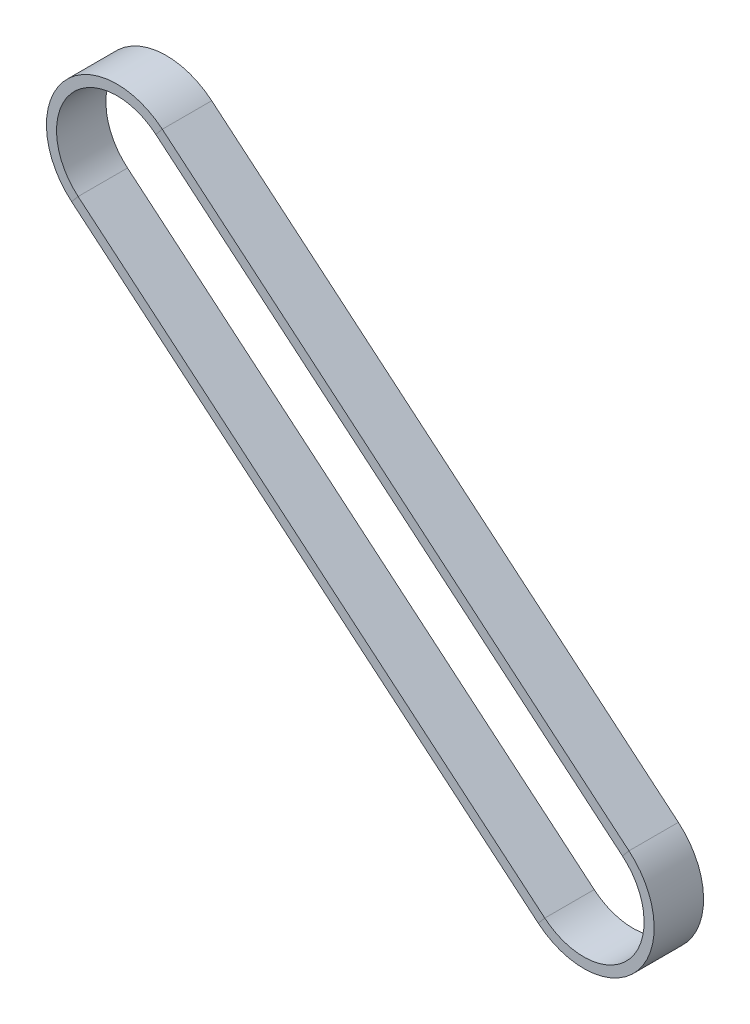
SolidWorks part; units mm, degrees
material "Rubber"
ref_plane "Front Plane" through (0, 0, 0) normal (0, 0, 1) x (1, 0, 0)
ref_plane "Top Plane" through (0, 0, 0) normal (0, 1, 0) x (1, 0, 0)
ref_plane "Right Plane" through (0, 0, 0) normal (1, 0, 0) x (0, 0, -1)
sketch "Sketch2" plane through (0, 0, 0) normal (0, 0, 1) x (1, 0, 0)
  line L0 (0, 0) -> (1, 0) construction
  line L1 (0, 0) -> (0, 1) construction
  line L2 (-13.1771, -15.7039) -> (-154.8954, 103.2118)
  line L3 (-128.5411, 134.6196) -> (13.1771, 15.7039)
  arc A0 (13.1771, 15.7039) -> (-13.1771, -15.7039) centre (0, 0) cw
  arc A1 (-154.8954, 103.2118) -> (-128.5411, 134.6196) centre (-141.7182, 118.9157) cw
ref_plane "Plane1" through (13.1771, 15.7039, 0) normal (0.766, -0.6428, 0) x (0, 0, -1)
sketch "Sketch3" plane through (13.1771, 15.7039, 0) normal (0.766, -0.6428, 0) x (0, 0, -1)
  line L5 (-7.5, 0.9167) -> (7.5, 0.9167)
  line L6 (-7.5, 0.9167) -> (-7.5, -2.1433)
  line L11 (-7.5, -2.1433) -> (7.5, -2.1433)
  line L12 (7.5, 0.9167) -> (7.5, -2.1433)
  point P0 (0, 0.4167)
  dimension "D1" = 15
  dimension "D2" = 3.06
sweep "Sweep2" add profiles "Sketch3" path "Sketch2"
